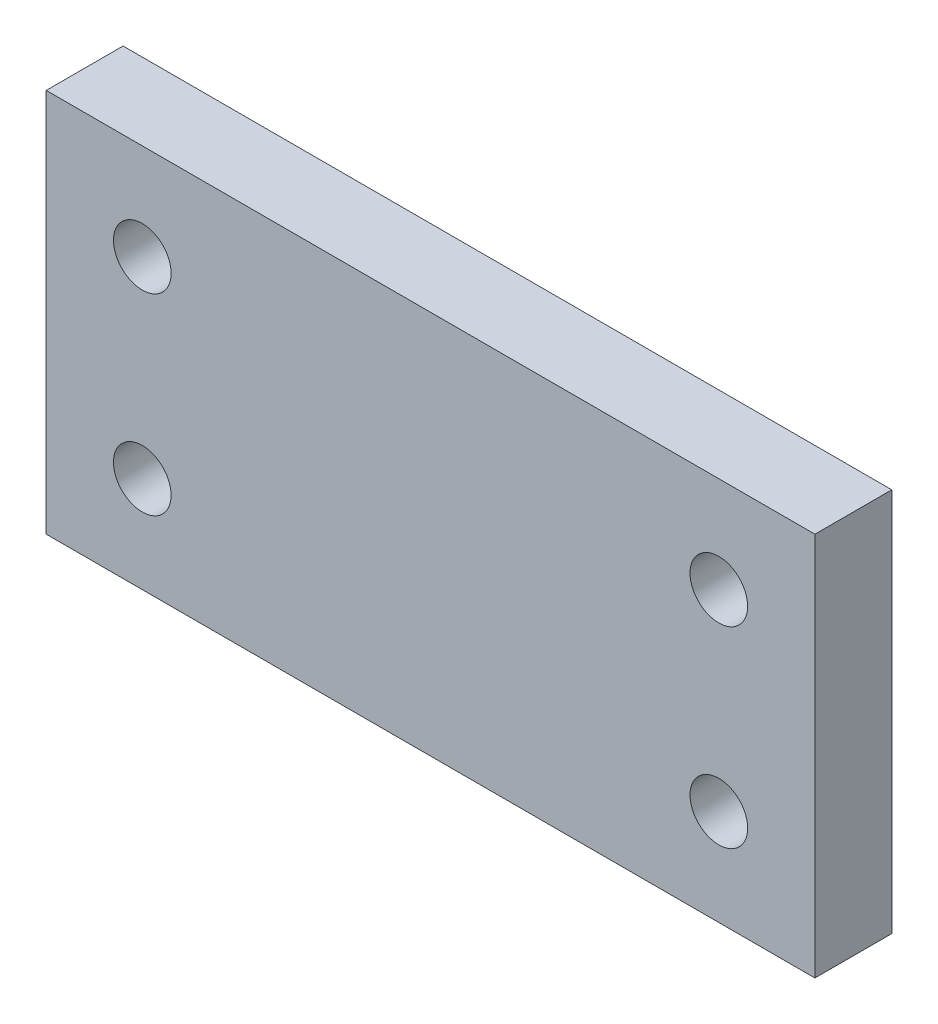
SolidWorks part; units mm, degrees
ref_plane "Piano frontale" through (0, 0, 0) normal (0, 0, 1) x (1, 0, 0)
ref_plane "Piano superiore" through (0, 0, 0) normal (0, 1, 0) x (1, 0, 0)
ref_plane "Piano destro" through (0, 0, 0) normal (1, 0, 0) x (0, 0, -1)
sketch "Schizzo1" plane through (0, 0, 0) normal (0, 0, 1) x (1, 0, 0)
  line L0 (0, 0) -> (0, -50000) construction
  line L1 (-40, 20) -> (40, 20)
  line L2 (-40, 20) -> (-40, -20)
  line L3 (-40, -20) -> (40, -20)
  line L4 (40, 20) -> (40, -20)
  line L5 (-40, 20) -> (40, -20) construction
  line L6 (-40, -20) -> (40, 20) construction
  line L7 (-40, 10) -> (49960, 10) construction
  line L8 (-40, -10) -> (49960, -10) construction
  line L9 (-40, 0) -> (49960, 0) construction
  line L10 (-30, 20) -> (-30, -49980) construction
  circle A0 centre (-30, 10) radius 3
  circle A1 centre (-30, -10) radius 3
  circle A2 centre (30, -10) radius 3
  circle A3 centre (30, 10) radius 3
  point P0 (0, 0)
  point P14 (-40, 0)
  dimension "D6" = 6
  dimension "D1" = 80
  dimension "D2" = 40
  dimension "D3" = 10
  dimension "D4" = 10
  dimension "D5" = 30
extrude "Estrusione-Estrusione1" add sketch "Schizzo1" along normal blind 8
